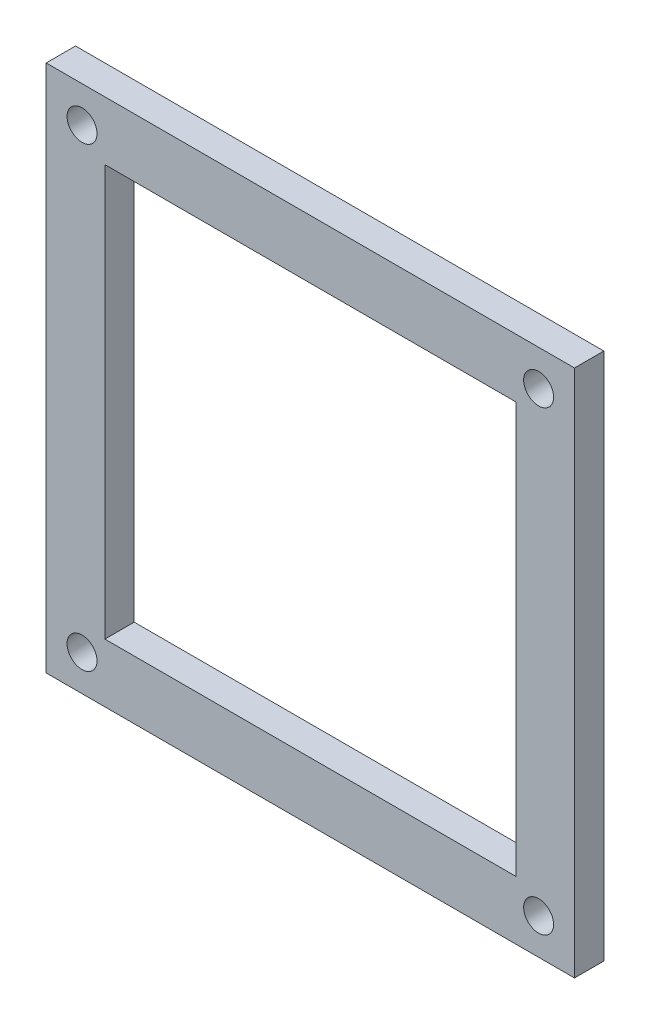
SolidWorks part; units mm, degrees
ref_plane "Front Plane" through (0, 0, 0) normal (0, 0, 1) x (1, 0, 0)
ref_plane "Top Plane" through (0, 0, 0) normal (0, 1, 0) x (1, 0, 0)
ref_plane "Right Plane" through (0, 0, 0) normal (1, 0, 0) x (0, 0, -1)
sketch "Sketch1" plane through (0, 0, 0) normal (0, 0, 1) x (1, 0, 0)
  line L0 (0, 45) -> (0, 0) construction
  line L1 (45, -45) -> (-45, -45)
  line L2 (45, -45) -> (45, 45)
  line L3 (45, 45) -> (-45, 45)
  line L4 (-45, -45) -> (-45, 45)
  line L5 (45, -45) -> (-45, 45) construction
  line L6 (45, 45) -> (-45, -45) construction
  line L7 (35, -35) -> (-35, -35)
  line L8 (35, -35) -> (35, 35)
  line L9 (35, 35) -> (-35, 35)
  line L10 (-35, -35) -> (-35, 35)
  line L11 (35, -35) -> (-35, 35) construction
  line L12 (35, 35) -> (-35, -35) construction
  line L13 (0, 0) -> (45, 0) construction
  circle A0 centre (-38.8909, 38.8909) radius 2.55
  circle A1 centre (38.8909, 38.8909) radius 2.55
  circle A2 centre (38.8909, -38.8909) radius 2.55
  circle A3 centre (-38.8909, -38.8909) radius 2.55
  point P0 (0, 0)
  point P6 (0, 0)
  dimension "D5" = 5.1
  dimension "D6" = 90
  dimension "D1" = 110
  dimension "D2" = 90
  dimension "D3" = 10
  dimension "D4" = 10
extrude "Boss-Extrude1" add sketch "Sketch1" along normal blind 5
